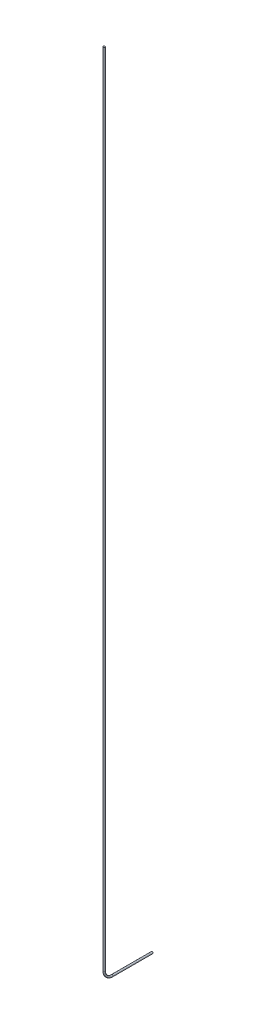
SolidWorks part; units mm, degrees
ref_plane "正面" through (0, 0, 0) normal (0, 0, 1) x (1, 0, 0)
ref_plane "平面" through (0, 0, 0) normal (0, 1, 0) x (1, 0, 0)
ref_plane "右側面" through (0, 0, 0) normal (1, 0, 0) x (0, 0, -1)
sketch "ｽｹｯﾁ1" plane through (0, 0, 0) normal (0, 0, 1) x (1, 0, 0)
  circle A0 centre (0, 0) radius 0.57
  dimension "D1" = 1.14
extrude "ﾎﾞｽ - 押し出し1" add sketch "ｽｹｯﾁ1" along normal blind 20
sketch "ｽｹｯﾁ2" plane through (0, 0, 20) normal (0, 0, 1) x (1, 0, 0)
  circle A1 centre (0, 0) radius 0.57
  circle A2 centre (0, 0) radius 0.57
  dimension "D1" = 0
sketch "ｽｹｯﾁ3" plane through (0, 0, 0) normal (1, 0, 0) x (0, 0, -1)
  line L0 (-20, 0) -> (-25, 0)
  line L1 (-20, 0.57) -> (-20, -0.57) construction
  line L2 (-30, 5) -> (-30, 505)
  line L3 (-20, 0.57) -> (-20, -0.57) construction
  arc A0 (-25, 0) -> (-30, 5) centre (-25, 5) cw
  point P8 (-30, 0)
  dimension "D2" = 5
  dimension "D1" = 10
  dimension "D3" = 500
sweep "ｽｲｰﾌﾟ1" add profiles "ｽｹｯﾁ2" path "ｽｹｯﾁ3"
